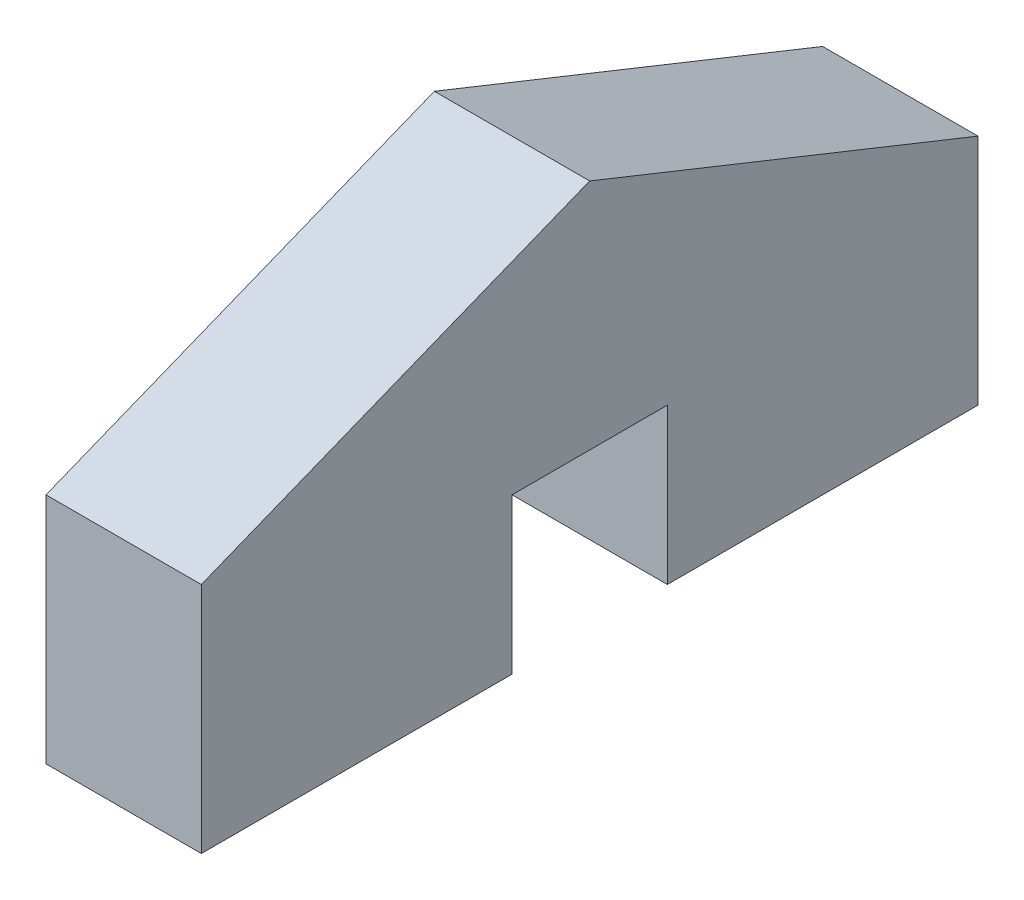
SolidWorks part; units mm, degrees
ref_plane "Front Plane" through (0, 0, 0) normal (0, 0, 1) x (1, 0, 0)
ref_plane "Top Plane" through (0, 0, 0) normal (0, 1, 0) x (1, 0, 0)
ref_plane "Right Plane" through (0, 0, 0) normal (1, 0, 0) x (0, 0, -1)
sketch "Sketch1" plane through (0, 0, 0) normal (1, 0, 0) x (0, 0, -1)
  line L0 (0, 0) -> (40, 0)
  line L2 (0, 0) -> (0, 30)
  line L4 (100, 0) -> (100, 30)
  line L5 (50, 50) -> (0, 30)
  line L6 (50, 50) -> (100, 30)
  line L8 (40, 0) -> (40, 20)
  line L9 (40, 20) -> (60, 20)
  line L10 (60, 0) -> (60, 20)
  line L16 (60, 0) -> (100, 0)
  dimension "D1" = 100
  dimension "D2" = 40
  dimension "D3" = 20
  dimension "D4" = 30
  dimension "D5" = 50
  dimension "D6" = 20
extrude "Boss-Extrude4" add sketch "Sketch1" along normal blind 20
